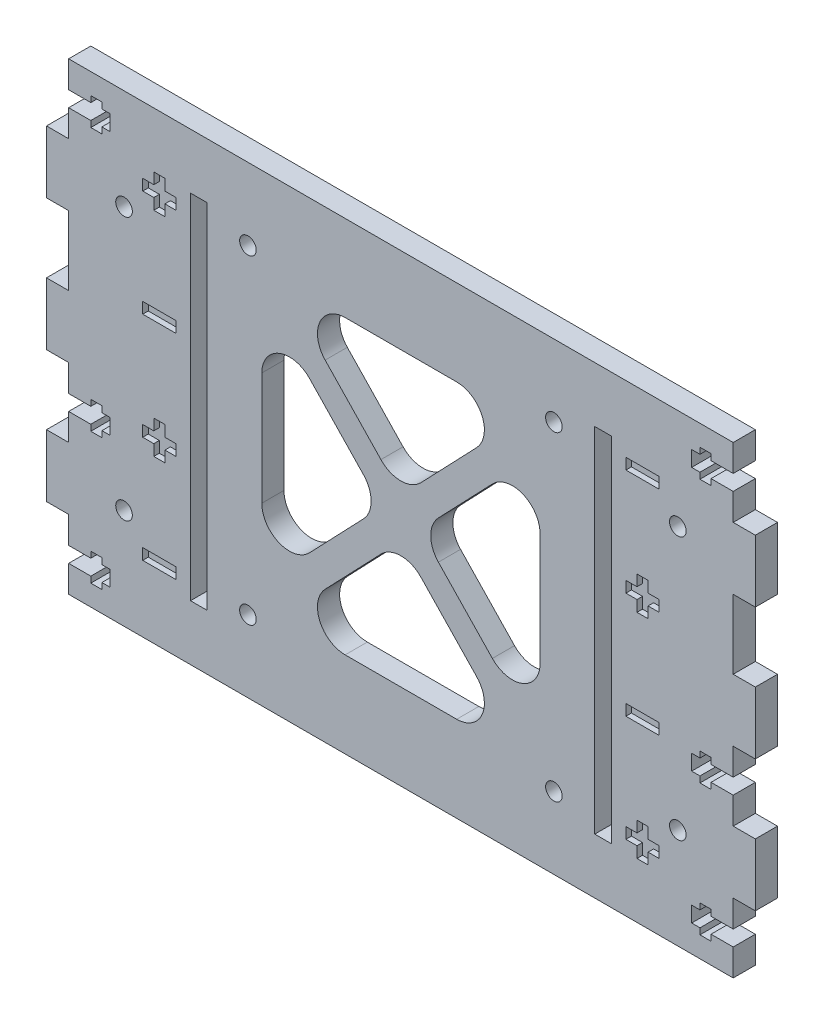
SolidWorks part; units mm, degrees
ref_plane "Спереди" through (0, 0, 0) normal (0, 0, 1) x (1, 0, 0)
ref_plane "Сверху" through (0, 0, 0) normal (0, 1, 0) x (1, 0, 0)
ref_plane "Справа" through (0, 0, 0) normal (1, 0, 0) x (0, 0, -1)
sketch "Эскиз1" plane through (0, 0, 0) normal (0, 0, 1) x (1, 0, 0)
  line L0 (-60, 5.625) -> (-64, 5.625)
  line L1 (-60, -41.875) -> (60, -41.875)
  line L2 (-60, -41.875) -> (-60, 41.875)
  line L3 (-60, 41.875) -> (60, 41.875)
  line L4 (60, -41.875) -> (60, 41.875)
  line L5 (-60, -41.875) -> (60, 41.875) construction
  line L6 (-60, 41.875) -> (60, -41.875) construction
  line L19 (-60, 5.625) -> (-60, -5.625)
  line L31 (-60, 29.375) -> (-64, 29.375)
  line L33 (-60, 29.375) -> (-60, 18.125)
  line L36 (-60, 18.125) -> (-64, 18.125)
  line L37 (-64, 29.375) -> (-64, 18.125)
  line L52 (-60, -5.625) -> (-64, -5.625)
  line L53 (-64, 5.625) -> (-64, -5.625)
  line L54 (-60, -18.125) -> (-64, -18.125)
  line L55 (-60, -18.125) -> (-60, -29.375)
  line L56 (-60, -29.375) -> (-64, -29.375)
  line L57 (-64, -18.125) -> (-64, -29.375)
  line L58 (0, -55) -> (0, 55) construction
  line L59 (64, -18.125) -> (64, -29.375)
  line L60 (60, -29.375) -> (64, -29.375)
  line L61 (60, -18.125) -> (60, -29.375)
  line L62 (60, -18.125) -> (64, -18.125)
  line L63 (64, 5.625) -> (64, -5.625)
  line L64 (60, -5.625) -> (64, -5.625)
  line L65 (64, 29.375) -> (64, 18.125)
  line L66 (60, 18.125) -> (64, 18.125)
  line L67 (60, 29.375) -> (60, 18.125)
  line L68 (60, 29.375) -> (64, 29.375)
  line L69 (60, 5.625) -> (60, -5.625)
  line L70 (60, 5.625) -> (64, 5.625)
  point P0 (0, 0)
  dimension "D1" = 120
  dimension "D2" = 83.75
  dimension "D3" = 4
  dimension "D4" = 11.25
  dimension "D5" = 12.5
  dimension "D7" = 12.5
  dimension "D6" = 3
extrude "Бобышка-Вытянуть1" add sketch "Эскиз1" along normal blind 4
sketch "Эскиз2" plane through (0, 0, 4) normal (0, 0, 1) x (1, 0, 0)
  line L0 (-60, -18.125) -> (-60, -5.625) construction
  line L1 (-60, 37.025) -> (-52.5, 37.025)
  line L2 (-60, 37.025) -> (-60, 34.225)
  line L3 (-60, 34.225) -> (-52.5, 34.225)
  line L4 (-52.5, 37.025) -> (-52.5, 34.225)
  line L6 (-56, 33.125) -> (-54, 33.125)
  line L7 (-56, 33.125) -> (-56, 38.125)
  line L8 (-56, 38.125) -> (-54, 38.125)
  line L9 (-54, 33.125) -> (-54, 38.125)
  line L10 (-56, 33.125) -> (-54, 38.125) construction
  line L11 (-56, 38.125) -> (-54, 33.125) construction
  line L12 (0, -2.2) -> (0, 2.2) construction
  line L13 (56, -9.375) -> (54, -14.375) construction
  line L22 (2.2, 0) -> (-2.2, 0) construction
  line L23 (56, -14.375) -> (54, -9.375) construction
  line L24 (56, -33.125) -> (54, -38.125) construction
  line L25 (-56, -38.125) -> (-54, -33.125) construction
  line L26 (-56, -33.125) -> (-54, -38.125) construction
  line L35 (-54, -33.125) -> (-54, -38.125)
  line L36 (-56, -38.125) -> (-54, -38.125)
  line L37 (-56, -33.125) -> (-56, -38.125)
  line L38 (-56, -33.125) -> (-54, -33.125)
  line L39 (-52.5, -37.025) -> (-52.5, -34.225)
  line L40 (-60, -34.225) -> (-52.5, -34.225)
  line L41 (-60, -37.025) -> (-60, -34.225)
  line L42 (-60, -37.025) -> (-52.5, -37.025)
  line L43 (-60, 29.375) -> (-60, 41.875) construction
  line L44 (-60, -13.275) -> (-52.5, -13.275)
  line L45 (-60, -13.275) -> (-60, -10.475)
  line L46 (-60, -10.475) -> (-52.5, -10.475)
  line L47 (-52.5, -13.275) -> (-52.5, -10.475)
  line L48 (56, -38.125) -> (54, -33.125) construction
  line L49 (-56, -14.375) -> (-54, -14.375)
  line L50 (-56, -14.375) -> (-56, -9.375)
  line L51 (-56, -9.375) -> (-54, -9.375)
  line L52 (-54, -14.375) -> (-54, -9.375)
  line L53 (-56, -14.375) -> (-54, -9.375) construction
  line L54 (-56, -9.375) -> (-54, -14.375) construction
  line L55 (56, 38.125) -> (54, 33.125) construction
  line L56 (56, 33.125) -> (54, 38.125) construction
  line L57 (54, -14.375) -> (54, -9.375)
  line L58 (56, -9.375) -> (54, -9.375)
  line L59 (56, -14.375) -> (56, -9.375)
  line L60 (56, -14.375) -> (54, -14.375)
  line L61 (52.5, -13.275) -> (52.5, -10.475)
  line L62 (60, -10.475) -> (52.5, -10.475)
  line L63 (60, -13.275) -> (60, -10.475)
  line L64 (60, -13.275) -> (52.5, -13.275)
  line L65 (60, -37.025) -> (52.5, -37.025)
  line L66 (60, -37.025) -> (60, -34.225)
  line L67 (60, -34.225) -> (52.5, -34.225)
  line L68 (52.5, -37.025) -> (52.5, -34.225)
  line L69 (56, -33.125) -> (54, -33.125)
  line L70 (56, -33.125) -> (56, -38.125)
  line L71 (56, -38.125) -> (54, -38.125)
  line L72 (54, -33.125) -> (54, -38.125)
  line L73 (54, 33.125) -> (54, 38.125)
  line L74 (56, 38.125) -> (54, 38.125)
  line L75 (56, 33.125) -> (56, 38.125)
  line L76 (56, 33.125) -> (54, 33.125)
  line L77 (52.5, 37.025) -> (52.5, 34.225)
  line L78 (60, 34.225) -> (52.5, 34.225)
  line L79 (60, 37.025) -> (60, 34.225)
  line L80 (60, 37.025) -> (52.5, 37.025)
  point P6 (-60, 35.625)
  point P8 (-55, 35.625)
  point P14 (-52.5, 35.625)
  point P45 (-55, -35.625)
  point P51 (-60, -11.875)
  point P52 (-55, -11.875)
  point P59 (-52.5, -11.875)
  point P66 (55, -11.875)
  point P67 (55, -35.625)
  point P68 (55, 35.625)
  dimension "D1" = 2.8
  dimension "D2" = 7.5
  dimension "D3" = 5
  dimension "D4" = 2
  dimension "D5" = 4
extrude "Вырез-Вытянуть1" cut sketch "Эскиз2" against normal blind 4 contours L4 L3 L2 L1 | L8 L9 L6 L7 | L51 L52 L49 L50 | L47 L46 L45 L44 | L38 L35 L36 L37 | L39 L40 L41 L42 | L69 L72 L71 L70 | L68 L67 L66 L65 | L58 L57 L60 L59 | L61 L62 L63 L64 | L74 L73 L76 L75 | L77 L78 L79 L80
sketch "Эскиз3" plane through (0, 0, 4) normal (0, 0, 1) x (1, 0, 0)
  line L0 (64, -18.125) -> (64, -29.375) construction
  line L1 (-27.625, -28.875) -> (27.625, -28.875) construction
  line L2 (-27.625, -28.875) -> (-27.625, 28.875) construction
  line L3 (-27.625, 28.875) -> (27.625, 28.875) construction
  line L4 (27.625, -28.875) -> (27.625, 28.875) construction
  line L5 (-27.625, -28.875) -> (27.625, 28.875) construction
  line L6 (-27.625, 28.875) -> (27.625, -28.875) construction
  line L8 (2.2, 0) -> (-2.2, 0) construction
  line L9 (0, -2.2) -> (0, 2.2) construction
  line L10 (38, 31.875) -> (35, -31.875) construction
  line L11 (-38, -31.875) -> (-35, -31.875)
  line L12 (-38, -31.875) -> (-38, 31.875)
  line L13 (-38, 31.875) -> (-35, 31.875)
  line L14 (-35, -31.875) -> (-35, 31.875)
  line L15 (-38, -31.875) -> (-35, 31.875) construction
  line L16 (-38, 31.875) -> (-35, -31.875) construction
  line L17 (38, -31.875) -> (35, 31.875) construction
  line L18 (35, -31.875) -> (35, 31.875)
  line L19 (38, 31.875) -> (35, 31.875)
  line L20 (38, -31.875) -> (38, 31.875)
  line L21 (38, -31.875) -> (35, -31.875)
  line L22 (-25.125, -26.375) -> (-25.125, -26.2619)
  line L26 (-25.125, -22.6455) -> (-3.4599, 0)
  line L27 (-25.125, -26.375) -> (21.7734, -26.375) construction
  line L29 (-25.125, -26.375) -> (-25.125, 22.6455) construction
  line L30 (-25.125, 22.6455) -> (21.7734, -26.375) construction
  line L40 (60, -34.225) -> (60, -29.375) construction
  line L46 (-25.125, -22.6455) -> (-25.125, 22.6455)
  line L47 (-25.125, 22.6455) -> (-3.4599, 0)
  line L48 (-25.125, -22.6455) -> (-25.125, 28.875) construction
  line L49 (-29.4314, 27.1468) -> (25.8186, -30.6032) construction
  line L50 (-21.7734, 26.375) -> (0, 3.6164)
  line L51 (-21.7734, 26.375) -> (21.7734, 26.375)
  line L52 (0, 3.6164) -> (21.7734, 26.375)
  line L53 (-25.125, -22.6455) -> (25.8186, 30.6032) construction
  line L54 (0, -3.6164) -> (21.7734, -26.375)
  line L55 (-21.7734, 26.375) -> (29.4314, -27.1468) construction
  line L56 (-21.7734, 26.375) -> (27.625, 26.375) construction
  line L57 (25.125, 22.6455) -> (3.4599, 0)
  line L58 (25.125, -22.6455) -> (25.125, 22.6455)
  line L59 (25.125, -22.6455) -> (3.4599, 0)
  line L60 (-21.7734, -26.375) -> (21.7734, -26.375)
  line L61 (-21.7734, -26.375) -> (0, -3.6164)
  circle A0 centre (-27.625, 28.875) radius 1.5
  circle A1 centre (27.625, 28.875) radius 1.5
  circle A2 centre (27.625, -28.875) radius 1.5
  circle A3 centre (-27.625, -28.875) radius 1.5
  circle A4 centre (50, -23.75) radius 1.5
  circle A6 centre (50, 23.75) radius 1.5
  circle A7 centre (-50, 23.75) radius 1.5
  circle A8 centre (-50, -23.75) radius 1.5
  point P0 (0, 0)
  point P15 (64, -23.75)
  point P30 (-36.5, 0)
  point P38 (36.5, 0)
  dimension "D3" = 3
  dimension "D4" = 3
  dimension "D1" = 57.75
  dimension "D2" = 55.25
  dimension "D5" = 3
  dimension "D6" = 3
  dimension "D7" = 36.5
  dimension "D12" = 10
  dimension "D8" = 2.5
  dimension "D10" = 2.5
  dimension "D11" = 2.5
  dimension "D9" = 2.5
extrude "Вырез-Вытянуть2" cut sketch "Эскиз3" against normal through all
fillet "Скругление1" radius 5 12 edges at (25.125, -22.6455, 2) (25.125, 22.6455, 2) (-21.7734, -26.375, 2) (21.7734, -26.375, 2) (-25.125, -22.6455, 2) (-25.125, 22.6455, 2) (3.4599, 0, 2) (0, -3.6164, 2) (-3.4599, 0, 2) (0, 3.6164, 2) (21.7734, 26.375, 2) (-21.7734, 26.375, 2)
sketch "Эскиз4" plane through (0, 0, 4) normal (0, 0, 1) x (1, 0, 0)
  line L0 (-46.625, 8.625) -> (-40.625, 8.625)
  line L1 (-46.625, 27.875) -> (-40.625, 27.875)
  line L2 (-46.625, 27.875) -> (-46.625, 29.875)
  line L3 (-46.625, 29.875) -> (-40.625, 29.875)
  line L4 (-40.625, 27.875) -> (-40.625, 29.875)
  line L5 (-46.625, 27.875) -> (-40.625, 29.875) construction
  line L6 (-46.625, 29.875) -> (-40.625, 27.875) construction
  line L7 (-44.625, 25.875) -> (-42.625, 25.875)
  line L8 (-44.625, 25.875) -> (-44.625, 31.875)
  line L9 (-44.625, 31.875) -> (-42.625, 31.875)
  line L10 (-42.625, 25.875) -> (-42.625, 31.875)
  line L11 (-44.625, 25.875) -> (-42.625, 31.875) construction
  line L12 (-44.625, 31.875) -> (-42.625, 25.875) construction
  line L13 (-46.625, 8.625) -> (-46.625, 10.625)
  line L14 (-46.625, 10.625) -> (-40.625, 10.625)
  line L15 (-40.625, 8.625) -> (-40.625, 10.625)
  line L16 (-44.625, 6.625) -> (-42.625, 6.625)
  line L17 (-44.625, 6.625) -> (-44.625, 12.625)
  line L18 (-44.625, 12.625) -> (-42.625, 12.625)
  line L19 (-42.625, 6.625) -> (-42.625, 12.625)
  line L20 (-46.625, 8.625) -> (-40.625, 10.625) construction
  line L21 (-46.625, 10.625) -> (-40.625, 8.625) construction
  line L22 (-44.625, 6.625) -> (-42.625, 12.625) construction
  line L23 (-44.625, 12.625) -> (-42.625, 6.625) construction
  line L24 (-46.625, -10.625) -> (-40.625, -10.625)
  line L25 (-46.625, -10.625) -> (-46.625, -8.625)
  line L26 (-46.625, -8.625) -> (-40.625, -8.625)
  line L27 (-40.625, -10.625) -> (-40.625, -8.625)
  line L28 (-44.625, -12.625) -> (-42.625, -12.625)
  line L29 (-44.625, -12.625) -> (-44.625, -6.625)
  line L30 (-44.625, -6.625) -> (-42.625, -6.625)
  line L31 (-42.625, -12.625) -> (-42.625, -6.625)
  line L32 (-46.625, -10.625) -> (-40.625, -8.625) construction
  line L33 (-46.625, -8.625) -> (-40.625, -10.625) construction
  line L34 (-44.625, -12.625) -> (-42.625, -6.625) construction
  line L35 (-44.625, -6.625) -> (-42.625, -12.625) construction
  line L36 (-46.625, -29.875) -> (-40.625, -29.875)
  line L37 (-46.625, -29.875) -> (-46.625, -27.875)
  line L38 (-46.625, -27.875) -> (-40.625, -27.875)
  line L39 (-40.625, -29.875) -> (-40.625, -27.875)
  line L40 (-44.625, -31.875) -> (-42.625, -31.875)
  line L41 (-44.625, -31.875) -> (-44.625, -25.875)
  line L42 (-44.625, -25.875) -> (-42.625, -25.875)
  line L43 (-42.625, -31.875) -> (-42.625, -25.875)
  line L44 (-46.625, -29.875) -> (-40.625, -27.875) construction
  line L45 (-46.625, -27.875) -> (-40.625, -29.875) construction
  line L46 (-44.625, -31.875) -> (-42.625, -25.875) construction
  line L47 (-44.625, -25.875) -> (-42.625, -31.875) construction
  line L48 (0, -2.2) -> (0, 2.2) construction
  line L49 (44.625, -25.875) -> (42.625, -31.875) construction
  line L50 (44.625, -31.875) -> (42.625, -25.875) construction
  line L51 (46.625, -27.875) -> (40.625, -29.875) construction
  line L52 (46.625, -29.875) -> (40.625, -27.875) construction
  line L53 (44.625, -6.625) -> (42.625, -12.625) construction
  line L54 (44.625, -12.625) -> (42.625, -6.625) construction
  line L55 (46.625, -8.625) -> (40.625, -10.625) construction
  line L56 (46.625, -10.625) -> (40.625, -8.625) construction
  line L57 (44.625, 12.625) -> (42.625, 6.625) construction
  line L58 (44.625, 6.625) -> (42.625, 12.625) construction
  line L59 (46.625, 10.625) -> (40.625, 8.625) construction
  line L60 (46.625, 8.625) -> (40.625, 10.625) construction
  line L61 (44.625, 31.875) -> (42.625, 25.875) construction
  line L62 (44.625, 25.875) -> (42.625, 31.875) construction
  line L63 (46.625, 29.875) -> (40.625, 27.875) construction
  line L64 (46.625, 27.875) -> (40.625, 29.875) construction
  line L65 (42.625, -31.875) -> (42.625, -25.875)
  line L66 (44.625, -25.875) -> (42.625, -25.875)
  line L67 (44.625, -31.875) -> (44.625, -25.875)
  line L68 (44.625, -31.875) -> (42.625, -31.875)
  line L69 (40.625, -29.875) -> (40.625, -27.875)
  line L70 (46.625, -27.875) -> (40.625, -27.875)
  line L71 (46.625, -29.875) -> (46.625, -27.875)
  line L72 (46.625, -29.875) -> (40.625, -29.875)
  line L73 (42.625, -12.625) -> (42.625, -6.625)
  line L74 (44.625, -6.625) -> (42.625, -6.625)
  line L75 (44.625, -12.625) -> (44.625, -6.625)
  line L76 (44.625, -12.625) -> (42.625, -12.625)
  line L77 (40.625, -10.625) -> (40.625, -8.625)
  line L78 (46.625, -8.625) -> (40.625, -8.625)
  line L79 (46.625, -10.625) -> (46.625, -8.625)
  line L80 (46.625, -10.625) -> (40.625, -10.625)
  line L81 (42.625, 6.625) -> (42.625, 12.625)
  line L82 (44.625, 12.625) -> (42.625, 12.625)
  line L83 (44.625, 6.625) -> (44.625, 12.625)
  line L84 (44.625, 6.625) -> (42.625, 6.625)
  line L85 (40.625, 8.625) -> (40.625, 10.625)
  line L86 (46.625, 10.625) -> (40.625, 10.625)
  line L87 (46.625, 8.625) -> (46.625, 10.625)
  line L88 (42.625, 25.875) -> (42.625, 31.875)
  line L89 (44.625, 31.875) -> (42.625, 31.875)
  line L90 (44.625, 25.875) -> (44.625, 31.875)
  line L91 (44.625, 25.875) -> (42.625, 25.875)
  line L92 (40.625, 27.875) -> (40.625, 29.875)
  line L93 (46.625, 29.875) -> (40.625, 29.875)
  line L94 (46.625, 27.875) -> (46.625, 29.875)
  line L95 (46.625, 27.875) -> (40.625, 27.875)
  line L96 (46.625, 8.625) -> (40.625, 8.625)
  point P0 (-43.625, 28.875)
  point P5 (-43.625, 28.875)
  point P11 (-27.625, 28.875)
  point P12 (-27.625, -28.875)
  point P14 (-43.625, 9.625)
  point P19 (-43.625, 9.625)
  point P24 (-43.625, -9.625)
  point P29 (-43.625, -9.625)
  point P34 (-43.625, -28.875)
  point P39 (-43.625, -28.875)
  point P79 (43.625, -28.875)
  point P80 (43.625, -9.625)
  point P81 (43.625, 9.625)
  point P82 (43.625, 28.875)
  dimension "D1" = 2
  dimension "D2" = 2
  dimension "D3" = 16
  dimension "D4" = 4
extrude "Вырез-Вытянуть3" cut sketch "Эскиз4" against normal blind 1 contours L9 L10 L7 L8 | L4 L3 L2 L1 | L15 L14 L13 L0 | L30 L31 L28 L29 | L27 L26 L25 L24 | L39 L38 L37 L36 | L94 L93 L92 L95 | L87 L86 L85 L96 | L82 L81 L84 L83 | L79 L78 L77 L80 | L71 L70 L69 L72 | L66 L65 L68 L67
